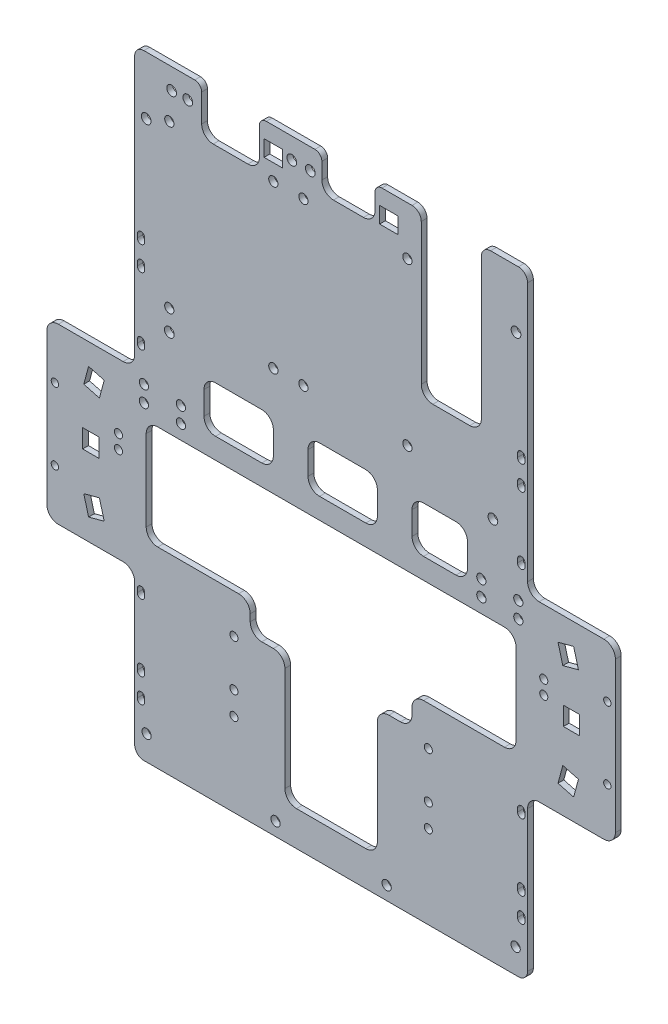
SolidWorks part; units mm, degrees
ref_plane "前视基准面" through (0, 0, 0) normal (0, 0, 1) x (1, 0, 0)
ref_plane "上视基准面" through (0, 0, 0) normal (0, 1, 0) x (1, 0, 0)
ref_plane "右视基准面" through (0, 0, 0) normal (1, 0, 0) x (0, 0, -1)
sketch "草图1" plane through (0, 0, 0) normal (0, 0, 1) x (1, 0, 0)
  line L0 (-126.7274, 110.9462) -> (-126.7274, 48.4462)
  line L1 (-126.7274, 48.4462) -> (-156.7274, 48.4462)
  line L2 (-156.7274, 48.4462) -> (-156.7274, -26.5538)
  line L3 (-156.7274, -26.5538) -> (-126.7274, -26.5538)
  line L4 (-126.7274, -26.5538) -> (-126.7274, -96.5538)
  line L5 (-126.7274, -96.5538) -> (43.2726, -96.5538)
  line L6 (43.2726, -96.5538) -> (43.2726, -26.5538)
  line L7 (43.2726, -26.5538) -> (73.2726, -26.5538)
  line L8 (73.2726, -26.5538) -> (73.2726, 48.4462)
  line L9 (73.2726, 48.4462) -> (43.2726, 48.4462)
  line L10 (43.2726, 48.4462) -> (43.2726, 123.4462)
  line L11 (-2.7274, 169.4462) -> (-126.7274, 169.4462)
  line L13 (-76.7274, -13.5538) -> (-6.7274, -13.5538)
  line L14 (43.2726, 123.4462) -> (43.2726, 169.4462)
  line L15 (43.2726, 169.4462) -> (23.2726, 169.4462)
  line L16 (-126.7274, 110.9462) -> (-126.7274, 169.4462)
  line L17 (-76.7274, -13.5538) -> (-76.7274, -26.5538)
  line L18 (23.2726, 169.4462) -> (23.2726, 99.4462)
  line L19 (23.2726, 99.4462) -> (-2.7274, 99.4462)
  line L20 (-2.7274, 169.4462) -> (-2.7274, 99.4462)
  line L21 (-76.7274, -26.5538) -> (-6.7274, -26.5538)
  line L22 (-6.7274, -13.5538) -> (-6.7274, -26.5538)
  dimension "D2" = 30
  dimension "D3" = 70
  dimension "D4" = 30
  dimension "D5" = 70
  dimension "D6" = 46
  dimension "D7" = 75
  dimension "D8" = 75
  dimension "D9" = 30
  dimension "D10" = 30
  dimension "D11" = 26
  dimension "D12" = 20
  dimension "D13" = 70
  dimension "D14" = 75
  dimension "D15" = 70
  dimension "D16" = 83
  dimension "D17" = 50
  dimension "D18" = 50
  dimension "D19" = 170
extrude "凸台-拉伸1" add sketch "草图1" along normal blind 2.5
sketch "草图2" plane through (0, 0, 2.5) normal (0, 0, 1) x (1, 0, 0)
  line L0 (43.2726, 48.4462) -> (43.2726, 169.4462) construction
  line L1 (38.9226, 99.4462) -> (38.9226, 97.8462)
  line L2 (43.2726, 48.4462) -> (43.2726, 169.4462) construction
  line L3 (42.1226, 99.4462) -> (42.1226, 97.8462)
  line L4 (-41.7274, -96.5538) -> (-41.7274, 49903.4462) construction
  line L5 (-126.7274, -96.5538) -> (43.2726, -96.5538) construction
  line L6 (43.2726, 169.4462) -> (23.2726, 169.4462) construction
  line L7 (43.2726, -96.5538) -> (43.2726, -26.5538) construction
  line L8 (38.9226, 88.9462) -> (38.9226, 87.3462)
  line L9 (42.1226, 88.9462) -> (42.1226, 87.3462)
  line L10 (38.9226, 59.9462) -> (38.9226, 58.3462)
  line L11 (42.1226, 59.9462) -> (42.1226, 58.3462)
  line L12 (38.9226, -33.4538) -> (38.9226, -35.0538)
  line L13 (42.1226, -33.4538) -> (42.1226, -35.0538)
  line L14 (38.9226, -62.4538) -> (38.9226, -64.0538)
  line L15 (42.1226, -62.4538) -> (42.1226, -64.0538)
  line L16 (38.9226, -72.9538) -> (38.9226, -74.5538)
  line L17 (42.1226, -72.9538) -> (42.1226, -74.5538)
  line L18 (-125.5774, -72.9538) -> (-125.5774, -74.5538)
  line L19 (-122.3774, -72.9538) -> (-122.3774, -74.5538)
  line L20 (-125.5774, -62.4538) -> (-125.5774, -64.0538)
  line L21 (-122.3774, -62.4538) -> (-122.3774, -64.0538)
  line L22 (-125.5774, -33.4538) -> (-125.5774, -35.0538)
  line L23 (-122.3774, -33.4538) -> (-122.3774, -35.0538)
  line L24 (-125.5774, 59.9462) -> (-125.5774, 58.3462)
  line L25 (-122.3774, 59.9462) -> (-122.3774, 58.3462)
  line L26 (-125.5774, 88.9462) -> (-125.5774, 87.3462)
  line L27 (-122.3774, 88.9462) -> (-122.3774, 87.3462)
  line L28 (-122.3774, 99.4462) -> (-122.3774, 97.8462)
  line L29 (-125.5774, 99.4462) -> (-125.5774, 97.8462)
  arc A1 (38.9226, -64.0538) -> (42.1226, -64.0538) centre (40.5226, -64.0538) ccw
  arc A2 (38.9226, -74.5538) -> (42.1226, -74.5538) centre (40.5226, -74.5538) ccw
  arc A3 (42.1226, 59.9462) -> (38.9226, 59.9462) centre (40.5226, 59.9462) ccw
  arc A4 (42.1226, 88.9462) -> (38.9226, 88.9462) centre (40.5226, 88.9462) ccw
  arc A5 (42.1226, 99.4462) -> (38.9226, 99.4462) centre (40.5226, 99.4462) ccw
  arc A12 (38.9226, -35.0538) -> (42.1226, -35.0538) centre (40.5226, -35.0538) ccw
  arc A14 (38.9226, 97.8462) -> (42.1226, 97.8462) centre (40.5226, 97.8462) ccw
  arc A15 (38.9226, 87.3462) -> (42.1226, 87.3462) centre (40.5226, 87.3462) ccw
  arc A16 (38.9226, 58.3462) -> (42.1226, 58.3462) centre (40.5226, 58.3462) ccw
  arc A17 (42.1226, -33.4538) -> (38.9226, -33.4538) centre (40.5226, -33.4538) ccw
  arc A18 (42.1226, -62.4538) -> (38.9226, -62.4538) centre (40.5226, -62.4538) ccw
  arc A19 (42.1226, -72.9538) -> (38.9226, -72.9538) centre (40.5226, -72.9538) ccw
  arc A20 (-125.5774, -72.9538) -> (-122.3774, -72.9538) centre (-123.9774, -72.9538) cw
  arc A21 (-122.3774, -74.5538) -> (-125.5774, -74.5538) centre (-123.9774, -74.5538) cw
  arc A22 (-125.5774, -62.4538) -> (-122.3774, -62.4538) centre (-123.9774, -62.4538) cw
  arc A23 (-122.3774, -64.0538) -> (-125.5774, -64.0538) centre (-123.9774, -64.0538) cw
  arc A24 (-125.5774, -33.4538) -> (-122.3774, -33.4538) centre (-123.9774, -33.4538) cw
  arc A25 (-122.3774, -35.0538) -> (-125.5774, -35.0538) centre (-123.9774, -35.0538) cw
  arc A26 (-125.5774, 59.9462) -> (-122.3774, 59.9462) centre (-123.9774, 59.9462) cw
  arc A27 (-122.3774, 58.3462) -> (-125.5774, 58.3462) centre (-123.9774, 58.3462) cw
  arc A28 (-125.5774, 88.9462) -> (-122.3774, 88.9462) centre (-123.9774, 88.9462) cw
  arc A29 (-122.3774, 87.3462) -> (-125.5774, 87.3462) centre (-123.9774, 87.3462) cw
  arc A30 (-125.5774, 99.4462) -> (-122.3774, 99.4462) centre (-123.9774, 99.4462) cw
  arc A31 (-122.3774, 97.8462) -> (-125.5774, 97.8462) centre (-123.9774, 97.8462) cw
  point P24 (-41.7274, -96.5538)
  dimension "D3" = 29
  dimension "D4" = 3.2
  dimension "D6" = 3.2
  dimension "D10" = 3.2
  dimension "D11" = 3.2
  dimension "D9" = 70
  dimension "D18" = 3.2
  dimension "D19" = 3.2
  dimension "D2" = 22
  dimension "D5" = 2.75
  dimension "D7" = 10.5
  dimension "D8" = 2.75
  dimension "D12" = 29
  dimension "D13" = 10.5
  dimension "D14" = 2.75
  dimension "D15" = 2.75
  dimension "D16" = 2.75
  dimension "D17" = 2.75
extrude "切除-拉伸1" cut sketch "草图2" against normal blind 10
sketch "草图3" plane through (0, 0, 2.5) normal (0, 0, 1) x (1, 0, 0)
  line L0 (-126.7274, 169.4462) -> (-126.7274, 48.4462) construction
  line L1 (-2.7274, 169.4462) -> (-126.7274, 169.4462) construction
  line L2 (43.2726, 169.4462) -> (23.2726, 169.4462) construction
  line L3 (43.2726, 48.4462) -> (43.2726, 169.4462) construction
  circle A0 centre (38.2726, 144.4462) radius 2.1
  circle A1 centre (-121.7274, 144.4462) radius 2.1
  circle A2 centre (28.2726, 69.4462) radius 2.1
  circle A3 centre (-111.7274, 69.4462) radius 2.1
  dimension "D1" = 4.2
  dimension "D4" = 4.2
  dimension "D9" = 4.2
  dimension "D10" = 4.2
  dimension "D2" = 5
  dimension "D3" = 25
  dimension "D5" = 25
  dimension "D6" = 5
  dimension "D7" = 100
  dimension "D8" = 100
  dimension "D11" = 15
  dimension "D12" = 15
extrude "切除-拉伸2" cut sketch "草图3" against normal blind 10
fillet "圆角1" radius 4 10 edges at (-126.7274, -96.5538, 1.25) (-156.7274, -26.5538, 1.25) (-156.7274, 48.4462, 1.25) (-126.7274, 169.4462, 1.25) (-2.7274, 169.4462, 1.25) (23.2726, 169.4462, 1.25) (43.2726, 169.4462, 1.25) (43.2726, -96.5538, 1.25) (73.2726, -26.5538, 1.25) (73.2726, 48.4462, 1.25)
sketch "草图4" plane through (0, 0, 2.5) normal (0, 0, 1) x (1, 0, 0)
  line L0 (-41.7274, -13.5538) -> (-121.7274, -13.5538)
  line L1 (-6.7274, -13.5538) -> (-76.7274, -13.5538) construction
  line L2 (-121.7274, -13.5538) -> (-121.7274, 31.4462)
  line L3 (-121.7274, 31.4462) -> (38.2726, 31.4462)
  line L4 (38.2726, 31.4462) -> (38.2726, -13.5538)
  line L5 (38.2726, -13.5538) -> (-41.7274, -13.5538)
  line L6 (-149.2274, 6.9462) -> (-149.2274, 14.9462)
  line L7 (-149.2274, 14.9462) -> (-142.2274, 14.9462)
  line L8 (-142.2274, 14.9462) -> (-142.2274, 6.9462)
  line L9 (-149.2274, 6.9462) -> (-142.2274, 6.9462)
  line L10 (-156.7274, 44.4462) -> (-156.7274, -22.5538) construction
  line L11 (-156.7274, 10.9462) -> (100.6093, 10.9462) construction
  line L12 (-41.7274, -96.5538) -> (-41.7274, 283.4292) construction
  line L13 (-122.7274, -96.5538) -> (39.2726, -96.5538) construction
  line L14 (-141.9659, -7.7421) -> (-148.7274, -9.5538)
  line L15 (-148.7274, -9.5538) -> (-146.6569, -17.2812)
  line L16 (-141.9659, -7.7421) -> (-139.8954, -15.4695)
  line L17 (-139.8954, -15.4695) -> (-146.6569, -17.2812)
  line L19 (-152.7274, -26.5538) -> (-126.7274, -26.5538) construction
  line L20 (-139.8954, 37.3619) -> (-146.6569, 39.1736)
  line L21 (-148.7274, 31.4462) -> (-146.6569, 39.1736)
  line L22 (-141.9659, 29.6344) -> (-139.8954, 37.3619)
  line L23 (-141.9659, 29.6344) -> (-148.7274, 31.4462)
  line L24 (58.5111, -7.7421) -> (56.4405, -15.4695)
  line L25 (58.5111, -7.7421) -> (65.2726, -9.5538)
  line L26 (65.2726, -9.5538) -> (63.202, -17.2812)
  line L27 (56.4405, -15.4695) -> (63.202, -17.2812)
  line L28 (65.7726, 6.9462) -> (65.7726, 14.9462)
  line L29 (65.7726, 14.9462) -> (58.7726, 14.9462)
  line L30 (58.7726, 14.9462) -> (58.7726, 6.9462)
  line L31 (65.7726, 6.9462) -> (58.7726, 6.9462)
  line L32 (58.5111, 29.6344) -> (56.4405, 37.3619)
  line L33 (58.5111, 29.6344) -> (65.2726, 31.4462)
  line L34 (65.2726, 31.4462) -> (63.202, 39.1736)
  line L35 (56.4405, 37.3619) -> (63.202, 39.1736)
  line L39 (-61.7274, -26.5538) -> (-61.7274, -81.5538)
  line L40 (-76.7274, -26.5538) -> (-6.7274, -26.5538) construction
  line L41 (-61.7274, -81.5538) -> (-21.7274, -81.5538)
  line L42 (-21.7274, -81.5538) -> (-21.7274, -26.5538)
  line L43 (-21.7274, -26.5538) -> (-41.7274, -26.5538)
  line L44 (-41.7274, -26.5538) -> (-61.7274, -26.5538)
  dimension "D1" = 80
  dimension "D2" = 80
  dimension "D3" = 45
  dimension "D4" = 14.5
  dimension "D5" = 7
  dimension "D6" = 8
  dimension "D7" = 4
  dimension "D8" = 7
  dimension "D9" = 8
  dimension "D10" = 17
  dimension "D11" = 8
  dimension "D12" = 15
  dimension "D13" = 20
  dimension "D14" = 20
  dimension "D15" = 15
extrude "切除-拉伸3" cut sketch "草图4" against normal through all
sketch "草图5" plane through (0, 0, 2.5) normal (0, 0, 1) x (1, 0, 0)
  line L0 (-41.7274, -119.2256) -> (-41.7274, 232.6988) construction
  line L5 (69.2726, 48.4462) -> (43.2726, 48.4462) construction
  line L6 (43.2726, 48.4462) -> (43.2726, 165.4462) construction
  line L7 (43.2726, 155.4462) -> (57.0396, 155.4462) construction
  line L12 (39.2726, 169.4462) -> (27.2726, 169.4462) construction
  line L13 (-126.7274, -26.5538) -> (-126.7274, -92.5538) construction
  line L14 (-12.7274, 162.4462) -> (-12.7274, 155.4462)
  line L15 (-12.7274, 155.4462) -> (-20.7274, 155.4462)
  line L16 (-20.7274, 155.4462) -> (-20.7274, 162.4462)
  line L17 (-20.7274, 162.4462) -> (-12.7274, 162.4462)
  line L19 (-62.7274, 155.4462) -> (-62.7274, 162.4462)
  line L20 (-70.7274, 155.4462) -> (-62.7274, 155.4462)
  line L21 (-70.7274, 162.4462) -> (-70.7274, 155.4462)
  line L22 (-62.7274, 162.4462) -> (-70.7274, 162.4462)
  line L27 (-2.7274, 99.4462) -> (-2.7274, 165.4462) construction
  line L29 (-6.7274, 169.4462) -> (-122.7274, 169.4462) construction
  circle A0 centre (-8.7274, 148.4462) radius 2
  circle A1 centre (-53.7274, 148.4462) radius 2
  circle A2 centre (-66.7274, 148.4462) radius 2
  circle A3 centre (-111.7274, 148.4462) radius 2
  circle A4 centre (-8.7274, 78.4462) radius 2
  circle A5 centre (-53.7274, 78.4462) radius 2
  circle A6 centre (-66.7274, 78.4462) radius 2
  circle A7 centre (-111.7274, 78.4462) radius 2
  circle A9 centre (39.2726, 44.4462) radius 2
  circle A11 centre (23.2726, 44.4462) radius 2
  circle A12 centre (23.2726, 37.6689) radius 2
  circle A13 centre (39.2726, 37.4462) radius 2
  circle A14 centre (-106.7274, 37.6689) radius 2
  circle A15 centre (-106.7274, 44.4462) radius 2
  circle A16 centre (-122.7274, 37.4462) radius 2
  circle A17 centre (-122.7274, 44.4462) radius 2
  dimension "D3" = 4
  dimension "D4" = 4
  dimension "D6" = 4
  dimension "D7" = 4
  dimension "D17" = 4
  dimension "D21" = 4
  dimension "D5" = 8
  dimension "D8" = 6
  dimension "D9" = 21
  dimension "D10" = 21
  dimension "D11" = 21
  dimension "D12" = 21
  dimension "D13" = 45
  dimension "D14" = 13
  dimension "D15" = 45
  dimension "D18" = 4
  dimension "D19" = 16
  dimension "D20" = 4
  dimension "D22" = 7
  dimension "D23" = 16
  dimension "D24" = 14
  dimension "D25" = 14
  dimension "D26" = 85
  dimension "D27" = 10
  dimension "D28" = 7
  dimension "D16" = 2
extrude "切除-拉伸4" cut sketch "草图5" against normal through all
sketch "草图7" plane through (0, 0, 2.5) normal (0, 0, 1) x (1, 0, 0)
  line L0 (-22.7274, 169.4462) -> (-22.7274, 154.4462)
  line L1 (-6.7274, 169.4462) -> (-122.7274, 169.4462) construction
  line L2 (-22.7274, 154.4462) -> (-45.7274, 154.4462)
  line L3 (-45.7274, 154.4462) -> (-45.7274, 169.4462)
  line L4 (-45.7274, 169.4462) -> (-22.7274, 169.4462)
  line L5 (-2.7274, 99.4462) -> (-2.7274, 165.4462) construction
  line L6 (-72.7274, 169.4462) -> (-72.7274, 149.4462)
  line L7 (-72.7274, 149.4462) -> (-97.7274, 149.4462)
  line L8 (-97.7274, 149.4462) -> (-97.7274, 169.4462)
  line L9 (-97.7274, 169.4462) -> (-72.7274, 169.4462)
  line L10 (-96.7274, 60.4462) -> (-96.7274, 40.4462)
  line L11 (-96.7274, 40.4462) -> (-66.7274, 40.4462)
  line L12 (-66.7274, 40.4462) -> (-66.7274, 60.4462)
  line L13 (-66.7274, 60.4462) -> (-96.7274, 60.4462)
  line L14 (-126.7274, 48.4462) -> (-152.7274, 48.4462) construction
  line L15 (-51.7274, 60.4462) -> (-51.7274, 40.4462)
  line L16 (-51.7274, 40.4462) -> (-21.7274, 40.4462)
  line L17 (-21.7274, 40.4462) -> (-21.7274, 60.4462)
  line L18 (-21.7274, 60.4462) -> (-51.7274, 60.4462)
  line L19 (17.2726, 60.4462) -> (17.2726, 40.4462)
  line L20 (17.2726, 40.4462) -> (-6.7274, 40.4462)
  line L21 (-6.7274, 40.4462) -> (-6.7274, 60.4462)
  line L22 (-6.7274, 60.4462) -> (17.2726, 60.4462)
  line L23 (23.2726, 165.4462) -> (23.2726, 99.4462) construction
  line L24 (-126.7274, 165.4462) -> (-126.7274, 48.4462) construction
  dimension "D1" = 20
  dimension "D2" = 43
  dimension "D3" = 15
  dimension "D4" = 70
  dimension "D5" = 95
  dimension "D6" = 8
  dimension "D7" = 12
  dimension "D8" = 30
  dimension "D9" = 30
  dimension "D10" = 6
  dimension "D11" = 15
  dimension "D12" = 15
  dimension "D13" = 30
extrude "切除-拉伸5" cut sketch "草图7" against normal through all contours L17 L18 L15 L16 | L22 L21 L20 L19 | L4 L3 L2 L0 | L9 L8 L7 L6 | L12 L13 L10 L11
sketch "草图8" plane through (0, 0, 2.5) normal (0, 0, 1) x (1, 0, 0)
  line L7 (43.2726, -92.5538) -> (43.2726, -26.5538) construction
  line L8 (-41.7274, -81.5538) -> (-41.7274, -106.8021) construction
  line L9 (-61.7274, -81.5538) -> (-21.7274, -81.5538) construction
  line L13 (-41.7274, -72.1752) -> (-41.7274, -39.0538) construction
  circle A12 centre (0.3226, -60.5538) radius 1.75
  circle A13 centre (0.3226, -50.5538) radius 1.75
  circle A15 centre (-83.7774, -60.5538) radius 1.75
  circle A16 centre (-83.7774, -50.5538) radius 1.75
  circle A18 centre (0.3226, -40.5538) radius 1.75 [skipped]
  circle A19 centre (0.3226, -30.5538) radius 1.75
  circle A20 centre (-83.7774, -30.5538) radius 1.75
  dimension "D5" = 3.5
  dimension "D7" = 42.95
  dimension "D17" = 3.5
  dimension "D6" = 20
  dimension "D3" = 21
  dimension "D4" = 10
  dimension "D19" = 42.95
  dimension "D20" = 3
extrude "切除-拉伸6" cut sketch "草图8" against normal through all
fillet "圆角2" radius 3 4 edges at (-22.7274, 169.4462, 1.25) (-72.7274, 169.4462, 1.25) (-97.7274, 169.4462, 1.25) (-45.7274, 169.4462, 1.25)
sketch "草图11" plane through (0, 0, 0) normal (0, 0, -1) x (-1, 0, 0)
  circle A0 centre (121.5684, -85.9029) radius 2
  circle A1 centre (65.7556, -90.762) radius 2
  circle A2 centre (17.6993, -90.762) radius 2
  circle A3 centre (-38.1135, -85.9029) radius 2
extrude "切除-拉伸9" cut sketch "草图11" against normal blind 10
fillet "圆角3" radius 5 34 edges at (-66.7274, 60.4462, 1.25) (-96.7274, 60.4462, 1.25) (-96.7274, 40.4462, 1.25) (-66.7274, 40.4462, 1.25) (17.2726, 40.4462, 1.25) (17.2726, 60.4462, 1.25) (-6.7274, 40.4462, 1.25) (-6.7274, 60.4462, 1.25) (-21.7274, 40.4462, 1.25) (-51.7274, 40.4462, 1.25) (-51.7274, 60.4462, 1.25) (-21.7274, 60.4462, 1.25) (38.2726, 31.4462, 1.25) (38.2726, -13.5538, 1.25) (-6.7274, -26.5538, 1.25) (-6.7274, -13.5538, 1.25) (-21.7274, -26.5538, 1.25) (-21.7274, -81.5538, 1.25) (-61.7274, -81.5538, 1.25) (-61.7274, -26.5538, 1.25) (-76.7274, -13.5538, 1.25) (-76.7274, -26.5538, 1.25) (-121.7274, -13.5538, 1.25) (-121.7274, 31.4462, 1.25) (-126.7274, -26.5538, 1.25) (43.2726, -26.5538, 1.25) (43.2726, 48.4462, 1.25) (-126.7274, 48.4462, 1.25) (-2.7274, 99.4462, 1.25) (23.2726, 99.4462, 1.25) (-22.7274, 154.4462, 1.25) (-45.7274, 154.4462, 1.25) (-72.7274, 149.4462, 1.25) (-97.7274, 149.4462, 1.25)
sketch "草图12" plane through (0, 0, 0) normal (0, 0, 1) x (1, 0, 0)
  line L0 (-152.7274, 48.4462) -> (-159.7274, 48.4462)
  line L1 (-164.7274, 43.4462) -> (-164.7274, -21.5538)
  line L2 (-159.7274, -26.5538) -> (-152.7274, -26.5538)
  line L3 (-156.7274, 44.4462) -> (-156.7274, -22.5538) construction
  line L4 (-156.7274, 44.4462) -> (-156.7274, -22.5538)
  line L5 (-41.7274, -96.5538) -> (-41.7274, -125.2103) construction
  line L6 (-122.7274, -96.5538) -> (39.2726, -96.5538) construction
  line L7 (73.2726, 44.4462) -> (73.2726, -22.5538)
  line L8 (76.2726, -26.5538) -> (69.2726, -26.5538)
  line L9 (81.2726, 43.4462) -> (81.2726, -21.5538)
  line L10 (69.2726, 48.4462) -> (76.2726, 48.4462)
  arc A0 (-156.7274, -22.5538) -> (-152.7274, -26.5538) centre (-152.7274, -22.5538) ccw construction
  arc A1 (-152.7274, 48.4462) -> (-156.7274, 44.4462) centre (-152.7274, 44.4462) ccw construction
  arc A2 (-156.7274, -22.5538) -> (-152.7274, -26.5538) centre (-152.7274, -22.5538) ccw
  arc A3 (-152.7274, 48.4462) -> (-156.7274, 44.4462) centre (-152.7274, 44.4462) ccw
  arc A4 (-159.7274, -26.5538) -> (-164.7274, -21.5538) centre (-159.7274, -21.5538) cw
  arc A5 (-164.7274, 43.4462) -> (-159.7274, 48.4462) centre (-159.7274, 43.4462) cw
  arc A6 (69.2726, 48.4462) -> (73.2726, 44.4462) centre (69.2726, 44.4462) cw
  arc A7 (73.2726, -22.5538) -> (69.2726, -26.5538) centre (69.2726, -22.5538) cw
  arc A8 (76.2726, -26.5538) -> (81.2726, -21.5538) centre (76.2726, -21.5538) ccw
  arc A9 (81.2726, 43.4462) -> (76.2726, 48.4462) centre (76.2726, 43.4462) ccw
  dimension "D2" = 5
  dimension "D1" = 8
extrude "凸台-拉伸3" add sketch "草图12" along normal up to surface (2.5 mm away) up to face at (-119.5684, -85.9029, 2.5)
sketch "草图13" plane through (0, 0, 2.5) normal (0, 0, 1) x (1, 0, 0)
  line L0 (81.2726, -21.5538) -> (81.2726, 43.4462) construction
  line L1 (76.2726, 48.4462) -> (48.2726, 48.4462) construction
  line L2 (48.2726, -26.5538) -> (76.2726, -26.5538) construction
  line L3 (-41.7274, -81.5538) -> (-41.7274, -59.8511) construction
  line L4 (-56.7274, -81.5538) -> (-26.7274, -81.5538) construction
  circle A0 centre (77.7726, 25.7862) radius 1.6
  circle A1 centre (77.7726, -5.2438) radius 1.6
  circle A2 centre (-161.2274, 25.7862) radius 1.6
  circle A3 centre (-161.2274, -5.2438) radius 1.6
  dimension "D1" = 3.5
  dimension "D3" = 3.2
  dimension "D4" = 21.31
  dimension "D6" = 3.2
  dimension "D2" = 22.66
  dimension "D5" = 3.5
extrude "切除-拉伸10" cut sketch "草图13" against normal through all
sketch "草图14" plane through (0, 0, 2.5) normal (0, 0, 1) x (1, 0, 0)
  line L0 (-121.7274, 26.4462) -> (-121.7274, -8.5538) construction
  line L1 (-48.7274, 169.4462) -> (-69.7274, 169.4462) construction
  line L2 (-131.7274, 48.4462) -> (-159.7274, 48.4462) construction
  line L3 (-41.7274, -81.5538) -> (-41.7274, -31.9455) construction
  line L4 (-56.7274, -81.5538) -> (-26.7274, -81.5538) construction
  line L5 (-45.7274, 159.4462) -> (-45.7274, 166.4462) construction
  line L6 (-97.7274, 154.4462) -> (-97.7274, 166.4462) construction
  line L7 (-100.7274, 169.4462) -> (-122.7274, 169.4462) construction
  circle A0 centre (-133.7274, 20.4462) radius 1.75
  circle A1 centre (-133.7274, 14.4462) radius 1.75
  circle A2 centre (50.2726, 14.4462) radius 1.75
  circle A3 centre (50.2726, 20.4462) radius 1.75
  circle A4 centre (-50.7274, 160.4462) radius 2.1
  circle A5 centre (-58.7274, 160.4462) radius 2.1
  circle A6 centre (-103.7274, 160.4462) radius 2.1
  circle A7 centre (-110.7274, 160.4462) radius 2.1
  dimension "D1" = 6
  dimension "D4" = 9
  dimension "D6" = 8
  dimension "D7" = 4.2
  dimension "D8" = 4.2
  dimension "D10" = 6
  dimension "D11" = 7
  dimension "D12" = 4.2
  dimension "D13" = 4.2
  dimension "D2" = 12
  dimension "D3" = 28
  dimension "D5" = 5
  dimension "D9" = 9
  dimension "D14" = 9
  dimension "D15" = 9
extrude "切除-拉伸11" cut sketch "草图14" against normal through all
